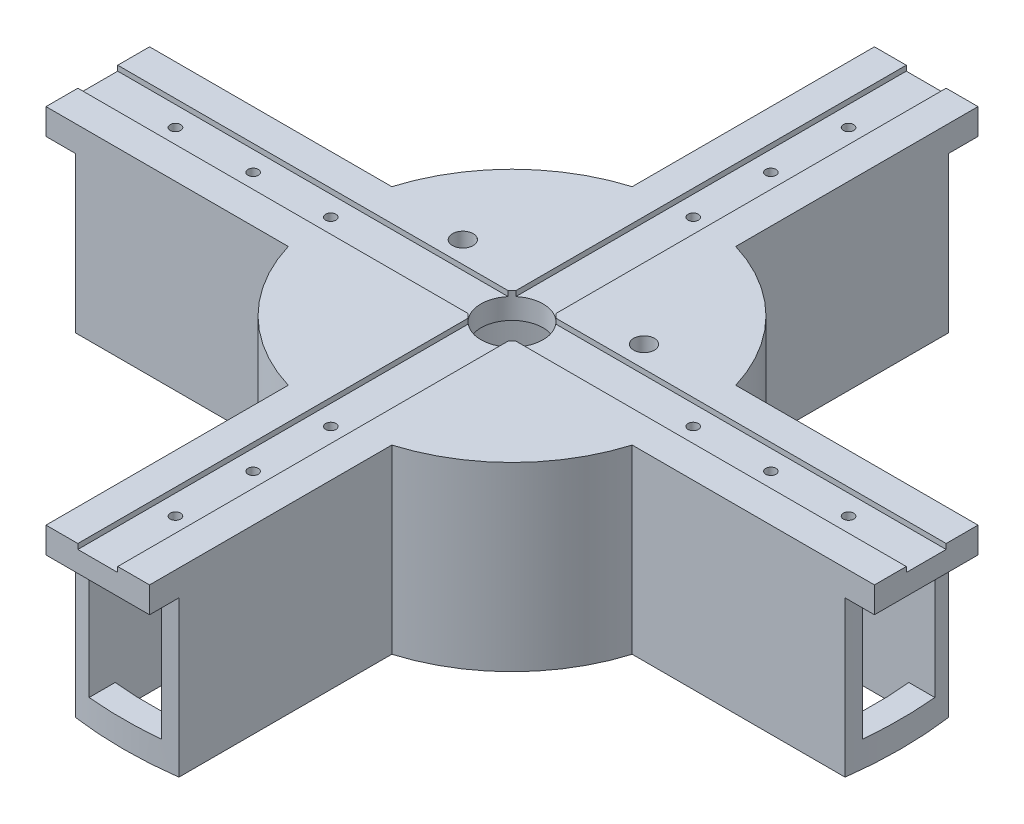
SolidWorks part; units mm, degrees
ref_plane "前视基准面" through (0, 0, 0) normal (0, 0, 1) x (1, 0, 0)
ref_plane "上视基准面" through (0, 0, 0) normal (0, 1, 0) x (1, 0, 0)
ref_plane "右视基准面" through (0, 0, 0) normal (1, 0, 0) x (0, 0, -1)
ref_plane "基准面4" through (0, -30, 0) normal (0, -1, 0) x (1, 0, 0)
sketch "草图1" plane through (0, -30, 0) normal (0, -1, 0) x (1, 0, 0)
  line L0 (-7, 74.6726) -> (-10, 74.6726)
  line L1 (-10, 74.6726) -> (-10, 33.2151)
  line L2 (-33.2151, 10) -> (-74.3303, 10)
  line L3 (-74.6726, 10) -> (-74.6726, 7)
  line L4 (-74.3303, -10) -> (-33.2151, -10)
  line L5 (-10, -33.2151) -> (-10, -74.3303)
  line L6 (10, -74.3303) -> (10, -33.2151)
  line L7 (33.2151, -10) -> (74.3303, -10)
  line L8 (74.6726, -10) -> (74.6726, -7)
  line L9 (74.3303, 10) -> (33.2151, 10)
  line L10 (10, 33.2151) -> (10, 74.3303)
  line L11 (-69.6491, 7) -> (-30.9049, 7)
  line L12 (-7, 30.9049) -> (-7, 69.6491)
  line L13 (7, 69.6491) -> (7, 30.9049)
  line L14 (30.9049, 7) -> (69.6491, 7)
  line L15 (69.6491, -7) -> (30.9049, -7)
  line L16 (7, -30.9049) -> (7, -69.6491)
  line L17 (-7, -69.6491) -> (-7, -30.9049)
  line L18 (-30.9049, -7) -> (-69.6491, -7)
  arc A0 (10, 74.3303) -> (-7, 74.6726) centre (0, 0) ccw
  arc A1 (-10, 33.2151) -> (-33.2151, 10) centre (0, 0) ccw
  arc A2 (-74.6726, 7) -> (-74.3303, -10) centre (0, 0) ccw
  arc A3 (-33.2151, -10) -> (-10, -33.2151) centre (0, 0) ccw
  arc A4 (-10, -74.3303) -> (10, -74.3303) centre (0, 0) ccw
  arc A5 (10, -33.2151) -> (33.2151, -10) centre (0, 0) ccw
  arc A6 (74.6726, -7) -> (74.3303, 10) centre (0, 0) ccw
  arc A7 (33.2151, 10) -> (10, 33.2151) centre (0, 0) ccw
  arc A8 (-30.9049, 7) -> (-7, 30.9049) centre (0, 0) cw
  arc A9 (-7, 69.6491) -> (7, 69.6491) centre (0, 0) cw
  arc A10 (7, 30.9049) -> (30.9049, 7) centre (0, 0) cw
  arc A11 (69.6491, 7) -> (69.6491, -7) centre (0, 0) cw
  arc A12 (30.9049, -7) -> (7, -30.9049) centre (0, 0) cw
  arc A13 (7, -69.6491) -> (-7, -69.6491) centre (0, 0) cw
  arc A14 (-7, -30.9049) -> (-30.9049, -7) centre (0, 0) cw
  arc A15 (-69.6491, -7) -> (-69.6491, 7) centre (0, 0) cw
  spline S0 degree 3 poles (-74.6726, 10) (-74.5585, 10) (-74.4444, 10) (-74.3303, 10) knots 0 0 0 0 1 1 1 1
  spline S1 degree 3 poles (74.6726, -10) (74.5585, -10) (74.4444, -10) (74.3303, -10) knots 0 0 0 0 1 1 1 1
extrude "凸台-拉伸1" add sketch "草图1" against normal blind 5
sketch "草图2" plane through (0, -25, 0) normal (0, 1, 0) x (-1, 0, 0)
  line L0 (74.6726, 7) -> (30.9049, 7)
  line L1 (7, 30.9049) -> (7, 74.6726)
  line L2 (7, 74.6726) -> (10, 74.6726)
  line L3 (10, 74.6726) -> (10, 33.2151)
  line L4 (33.2151, 10) -> (74.6726, 10)
  line L5 (74.6726, 10) -> (74.6726, 7)
  arc A0 (30.9049, 7) -> (7, 30.9049) centre (0, 0) ccw
  arc A1 (10, 33.2151) -> (33.2151, 10) centre (0, 0) cw
extrude "凸台-拉伸2" add sketch "草图2" along normal blind 25
sketch "草图3" plane through (0, -25, 0) normal (0, 1, 0) x (-1, 0, 0)
  line L0 (-74.6726, -7) -> (-30.9049, -7)
  line L1 (-7, -30.9049) -> (-7, -74.6726)
  line L2 (-10, -74.3303) -> (-10, -33.2151)
  line L3 (-33.2151, -10) -> (-74.6726, -10)
  line L4 (-74.6726, -10) -> (-74.6726, -7)
  arc A0 (-30.9049, -7) -> (-7, -30.9049) centre (0, 0) ccw
  arc A1 (-7, -74.6726) -> (-10, -74.3303) centre (0, 0) cw
  arc A2 (-10, -33.2151) -> (-33.2151, -10) centre (0, 0) cw
extrude "凸台-拉伸3" add sketch "草图3" along normal blind 25
sketch "草图4" plane through (0, -25, 0) normal (0, 1, 0) x (-1, 0, 0)
  line L0 (-30.9049, 7) -> (-74.6726, 7)
  line L1 (-74.3303, 10) -> (-33.2151, 10)
  line L2 (-10, 33.2151) -> (-10, 74.3303)
  line L3 (-7, 74.6726) -> (-7, 30.9049)
  arc A0 (-74.6726, 7) -> (-74.3303, 10) centre (0, 0) cw
  arc A1 (-33.2151, 10) -> (-10, 33.2151) centre (0, 0) cw
  arc A2 (-10, 74.3303) -> (-7, 74.6726) centre (0, 0) cw
  arc A3 (-7, 30.9049) -> (-30.9049, 7) centre (0, 0) ccw
extrude "凸台-拉伸4" add sketch "草图4" along normal blind 25
sketch "草图5" plane through (0, -25, 0) normal (0, 1, 0) x (-1, 0, 0)
  line L0 (30.9049, -7) -> (74.6726, -7)
  line L1 (74.3303, -10) -> (33.2151, -10)
  line L2 (10, -33.2151) -> (10, -74.3303)
  line L3 (7, -74.6726) -> (7, -30.9049)
  arc A0 (74.6726, -7) -> (74.3303, -10) centre (0, 0) cw
  arc A1 (33.2151, -10) -> (10, -33.2151) centre (0, 0) cw
  arc A2 (10, -74.3303) -> (7, -74.6726) centre (0, 0) cw
  arc A3 (7, -30.9049) -> (30.9049, -7) centre (0, 0) ccw
extrude "凸台-拉伸5" add sketch "草图5" along normal blind 25
sketch "草图6" plane through (0, 0, 0) normal (0, 1, 0) x (-1, 0, 0)
  line L0 (-74.6726, -10) -> (-74.6726, 7)
  line L1 (-74.3303, 10) -> (-33.2151, 10)
  line L2 (-10, 33.2151) -> (-10, 74.6726)
  line L3 (-10, 74.6726) -> (10, 74.6726)
  line L4 (10, 74.6726) -> (10, 33.2151)
  line L5 (33.2151, 10) -> (74.3303, 10)
  line L6 (74.6726, 10) -> (74.6726, -7)
  line L7 (74.3303, -10) -> (33.2151, -10)
  line L8 (10, -33.2151) -> (10, -74.6726)
  line L9 (10, -74.6726) -> (-10, -74.6726)
  line L10 (-10, -74.6726) -> (-10, -33.2151)
  line L11 (-33.2151, -10) -> (-74.3303, -10)
  arc A0 (-74.6726, 7) -> (-74.3303, 10) centre (0, 0) cw
  arc A1 (-33.2151, 10) -> (-10, 33.2151) centre (0, 0) cw
  arc A2 (10, 33.2151) -> (33.2151, 10) centre (0, 0) cw
  arc A3 (74.6726, -7) -> (74.3303, -10) centre (0, 0) cw
  arc A4 (33.2151, -10) -> (10, -33.2151) centre (0, 0) cw
  arc A5 (-10, -33.2151) -> (-33.2151, -10) centre (0, 0) cw
  spline S0 degree 3 poles (74.6726, 10) (74.5585, 10) (74.4444, 10) (74.3303, 10) knots 0 0 0 0 1 1 1 1
  spline S1 degree 3 poles (-74.6726, -10) (-74.5585, -10) (-74.4444, -10) (-74.3303, -10) knots 0 0 0 0 1 1 1 1
extrude "凸台-拉伸6" add sketch "草图6" along normal blind 5
sketch "草图7" plane through (0, 5, 0) normal (0, 1, 0) x (-1, 0, 0)
  line L0 (3.85, -3.85) -> (74.3303, -3.85)
  line L1 (74.6726, -3.85) -> (74.6726, 3.85)
  line L2 (74.3303, 3.85) -> (3.85, 3.85)
  line L3 (3.85, 3.85) -> (3.85, 74.6726)
  line L4 (3.85, 74.6726) -> (-3.85, 74.6726)
  line L5 (-3.85, 74.6726) -> (-3.85, 3.85)
  line L6 (-3.85, 3.85) -> (-74.3303, 3.85)
  line L7 (-74.6726, 3.85) -> (-74.6726, -3.85)
  line L8 (-74.3303, -3.85) -> (-3.85, -3.85)
  line L9 (-3.85, -3.85) -> (-3.85, -74.6726)
  line L10 (-3.85, -74.6726) -> (3.85, -74.6726)
  line L11 (3.85, -74.6726) -> (3.85, -3.85)
  spline S0 degree 3 poles (74.6726, -3.85) (74.5585, -3.85) (74.4444, -3.85) (74.3303, -3.85) knots 0 0 0 0 1 1 1 1
  spline S1 degree 3 poles (74.6726, 3.85) (74.5585, 3.85) (74.4444, 3.85) (74.3303, 3.85) knots 0 0 0 0 1 1 1 1
  spline S2 degree 3 poles (-74.6726, 3.85) (-74.5585, 3.85) (-74.4444, 3.85) (-74.3303, 3.85) knots 0 0 0 0 1 1 1 1
  spline S3 degree 3 poles (-74.6726, -3.85) (-74.5585, -3.85) (-74.4444, -3.85) (-74.3303, -3.85) knots 0 0 0 0 1 1 1 1
extrude "切除-拉伸1" cut sketch "草图7" against normal blind 1
sketch "草图8" plane through (0, -30, 0) normal (0, -1, 0) x (1, 0, 0)
  line L0 (-7, 74.6726) -> (-10, 74.6726)
  line L1 (-10, 74.6726) -> (-10, 74.3303)
  arc A0 (-10, 74.3303) -> (-7, 74.6726) centre (0, 0) cw
extrude "切除-拉伸2" cut sketch "草图8" against normal blind 5
sketch "草图9" plane through (0, -30, 0) normal (0, -1, 0) x (1, 0, 0)
  line L0 (-74.6726, 10) -> (-74.6726, 7)
  arc A0 (-74.6726, 7) -> (-74.3303, 10) centre (0, 0) cw
  spline S0 degree 3 poles (-74.6726, 10) (-74.5585, 10) (-74.4444, 10) (-74.3303, 10) knots 0 0 0 0 1 1 1 1
extrude "切除-拉伸3" cut sketch "草图9" against normal blind 5
sketch "草图10" plane through (0, -30, 0) normal (0, -1, 0) x (1, 0, 0)
  line L0 (74.6726, -10) -> (74.6726, -7)
  arc A0 (74.6726, -7) -> (74.3303, -10) centre (0, 0) cw
  spline S0 degree 3 poles (74.6726, -10) (74.5585, -10) (74.4444, -10) (74.3303, -10) knots 0 0 0 0 1 1 1 1
extrude "切除-拉伸4" cut sketch "草图10" against normal blind 5
sketch "草图11" plane through (0, -25, 0) normal (0, -1, 0) x (1, 0, 0)
  line L0 (-74.6726, 10) -> (-74.6726, 7)
  arc A0 (-74.6726, 7) -> (-74.3303, 10) centre (0, 0) cw
  spline S0 degree 3 poles (-74.6726, 10) (-74.5585, 10) (-74.4444, 10) (-74.3303, 10) knots 0 0 0 0 1 1 1 1
extrude "切除-拉伸5" cut sketch "草图11" against normal blind 25
sketch "草图12" plane through (-74.6726, 0, 0) normal (-1, 0, 0) x (0, 0, 1)
  line L0 (-3.85, 5) -> (-7, 5)
  line L1 (-7, 5) -> (-7, 0)
  line L2 (-7, 0) -> (7, 0)
  line L3 (7, 0) -> (10, 0)
  line L4 (10, 0) -> (10, 5)
  line L5 (10, 5) -> (3.85, 5)
  line L6 (3.85, 5) -> (3.85, 4)
  line L7 (3.85, 4) -> (-3.85, 4)
  line L8 (-3.85, 4) -> (-3.85, 5)
extrude "切除-拉伸6" cut sketch "草图12" against normal blind 0.3423
sketch "草图13" plane through (0, 5, 0) normal (0, 1, 0) x (-1, 0, 0)
  line L0 (74.6726, -7) -> (74.3303, -7)
  line L1 (74.3303, -7) -> (74.3303, -10)
  arc A0 (74.3303, -10) -> (74.6726, -7) centre (0, 0) ccw
extrude "切除-拉伸7" cut sketch "草图13" against normal blind 5
sketch "草图14" plane through (-74.3303, 0, 0) normal (-1, 0, 0) x (0, 0, 1)
  line L0 (3.85, 4) -> (3.85, 5)
  line L1 (3.85, 5) -> (10, 5)
  line L2 (10, 5) -> (10, 0)
  line L3 (10, 0) -> (7, 0)
  line L4 (7, 0) -> (-7, 0)
  line L5 (-7, 0) -> (-10, 0)
  line L6 (-10, 0) -> (-10, 5)
  line L7 (-10, 5) -> (-3.85, 5)
  line L8 (-3.85, 5) -> (-3.85, 4)
  line L9 (-3.85, 4) -> (3.85, 4)
extrude "凸台-拉伸7" add sketch "草图14" along normal blind 0.3423
sketch "草图15" plane through (0, -25, 0) normal (0, -1, 0) x (1, 0, 0)
  line L0 (74.6726, -10) -> (74.6726, -7)
  arc A0 (74.6726, -7) -> (74.3303, -10) centre (0, 0) cw
  spline S0 degree 3 poles (74.6726, -10) (74.5585, -10) (74.4444, -10) (74.3303, -10) knots 0 0 0 0 1 1 1 1
extrude "切除-拉伸8" cut sketch "草图15" against normal blind 25
sketch "草图16" plane through (74.6726, 0, 0) normal (1, 0, 0) x (0, 0, -1)
  line L0 (-3.85, 5) -> (-7, 5)
  line L1 (-7, 5) -> (-7, 0)
  line L2 (-7, 0) -> (7, 0)
  line L3 (7, 0) -> (10, 0)
  line L4 (10, 0) -> (10, 5)
  line L5 (10, 5) -> (3.85, 5)
  line L6 (3.85, 5) -> (3.85, 4)
  line L7 (3.85, 4) -> (-3.85, 4)
  line L8 (-3.85, 4) -> (-3.85, 5)
extrude "切除-拉伸9" cut sketch "草图16" against normal blind 0.3423
sketch "草图17" plane through (0, 5, 0) normal (0, 1, 0) x (-1, 0, 0)
  line L0 (-74.6726, 7) -> (-74.3303, 7)
  line L1 (-74.3303, 7) -> (-74.3303, 10)
  arc A0 (-74.3303, 10) -> (-74.6726, 7) centre (0, 0) ccw
extrude "切除-拉伸10" cut sketch "草图17" against normal blind 5
sketch "草图18" plane through (74.3303, 0, 0) normal (1, 0, 0) x (0, 0, -1)
  line L0 (-3.85, 5) -> (-3.85, 4)
  line L1 (-3.85, 4) -> (3.85, 4)
  line L2 (3.85, 4) -> (3.85, 5)
  line L3 (3.85, 5) -> (10, 5)
  line L4 (10, 5) -> (10, 0)
  line L5 (10, 0) -> (7, 0)
  line L6 (7, 0) -> (-7, 0)
  line L7 (-7, 0) -> (-10, 0)
  line L8 (-10, 0) -> (-10, 5)
  line L9 (-10, 5) -> (-3.85, 5)
extrude "凸台-拉伸8" add sketch "草图18" along normal blind 0.3423
sketch "草图19" plane through (0, 0, -74.6726) normal (0, 0, -1) x (-1, 0, 0)
  line L0 (3.85, 4) -> (3.85, 5)
  line L1 (3.85, 5) -> (10, 5)
  line L2 (10, 5) -> (10, 0)
  line L3 (10, 0) -> (-10, 0)
  line L4 (-10, 0) -> (-10, 5)
  line L5 (-10, 5) -> (-3.85, 5)
  line L6 (-3.85, 5) -> (-3.85, 4)
  line L7 (-3.85, 4) -> (3.85, 4)
extrude "凸台-拉伸9" add sketch "草图19" along normal blind 5.3274
sketch "草图20" plane through (74.6726, 0, 0) normal (1, 0, 0) x (0, 0, -1)
  line L0 (-3.85, 5) -> (-3.85, 4)
  line L1 (-3.85, 4) -> (3.85, 4)
  line L2 (3.85, 4) -> (3.85, 5)
  line L3 (3.85, 5) -> (10, 5)
  line L4 (10, 5) -> (10, 0)
  line L5 (10, 0) -> (-10, 0)
  line L6 (-10, 0) -> (-10, 5)
  line L7 (-10, 5) -> (-3.85, 5)
extrude "凸台-拉伸10" add sketch "草图20" along normal blind 5.3274
sketch "草图21" plane through (-74.6726, 0, 0) normal (-1, 0, 0) x (0, 0, 1)
  line L0 (3.85, 4) -> (3.85, 5)
  line L1 (3.85, 5) -> (10, 5)
  line L2 (10, 5) -> (10, 0)
  line L3 (10, 0) -> (-10, 0)
  line L4 (-10, 0) -> (-10, 5)
  line L5 (-10, 5) -> (-3.85, 5)
  line L6 (-3.85, 5) -> (-3.85, 4)
  line L7 (-3.85, 4) -> (3.85, 4)
extrude "凸台-拉伸11" add sketch "草图21" along normal blind 5.3274
sketch "草图22" plane through (0, -25, 0) normal (0, -1, 0) x (1, 0, 0)
  line L0 (-7, 74.6726) -> (-10, 74.6726)
  line L1 (-10, 74.6726) -> (-10, 74.3303)
  arc A0 (-10, 74.3303) -> (-7, 74.6726) centre (0, 0) cw
extrude "切除-拉伸11" cut sketch "草图22" against normal blind 25
sketch "草图23" plane through (0, 0, 74.6726) normal (0, 0, 1) x (1, 0, 0)
  line L0 (3.85, 4) -> (3.85, 5)
  line L1 (3.85, 5) -> (10, 5)
  line L2 (10, 5) -> (10, 0)
  line L3 (10, 0) -> (-10, 0)
  line L4 (-10, 0) -> (-10, 5)
  line L5 (-10, 5) -> (-3.85, 5)
  line L6 (-3.85, 5) -> (-3.85, 4)
  line L7 (-3.85, 4) -> (3.85, 4)
extrude "凸台-拉伸12" add sketch "草图23" along normal blind 5.3274
hole_wizard "Ø2.0 (2) 直径孔1" positions "草图25" profile "草图24" hole size "Ø2.0" standard "ANSI Metric"
sketch "草图25" plane through (0, 0, 0) normal (0, -1, 0) x (-1, 0, 0)
  point P0 (-50, 0)
  point P1 (-35, 0)
  point P2 (-65, 0)
  point P3 (50, 0)
  point P4 (35, 0)
  point P5 (65, 0)
sketch "草图24" plane through (50, 0, 0) normal (1, 0, 0) x (0, 0, -1)
  line L0 (0, 0) -> (0, 5)
  line L1 (0, 5) -> (1, 5)
  line L2 (1, 5) -> (1, 0)
  line L5 (1, 0) -> (0, 0)
  line L11 (0, -6.35) -> (0, 107.95) construction
  dimension "通孔孔直径" = 2
  dimension "通孔孔深度" = 5
hole_wizard "Ø12.0 (12) 直径孔1" positions "草图27" profile "草图26" hole size "Ø12.0" standard "ANSI Metric"
sketch "草图27" plane through (0, 0, 0) normal (0, -1, 0) x (-1, 0, 0)
  point P0 (0, 0)
sketch "草图26" plane through (0, 0, 0) normal (1, 0, 0) x (0, 0, -1)
  line L0 (0, 0) -> (0, 5)
  line L1 (0, 5) -> (6, 5)
  line L2 (6, 5) -> (6, 0)
  line L5 (6, 0) -> (0, 0)
  line L11 (0, -6.35) -> (0, 107.95) construction
  dimension "通孔孔直径" = 12
  dimension "通孔孔深度" = 5
hole_wizard "Ø2.0 (2) 直径孔2" positions "草图29" profile "草图28" hole size "Ø2.0" standard "ANSI Metric"
sketch "草图29" plane through (0, 4, 0) normal (0, 1, 0) x (1, 0, 0)
  point P0 (0, -65)
  point P1 (0, 65)
  point P2 (0, 35)
  point P3 (0, 50)
  point P4 (0, -50)
  point P5 (0, -35)
sketch "草图28" plane through (0, 4, 65) normal (1, 0, 0) x (0, 0, 1)
  line L0 (0, 0) -> (0, 34)
  line L1 (0, 34) -> (1, 34)
  line L2 (1, 34) -> (1, 0)
  line L5 (1, 0) -> (0, 0)
  line L11 (0, -6.35) -> (0, 107.95) construction
  dimension "通孔孔直径" = 2
  dimension "通孔孔深度" = 34
hole_wizard "Ø4.0 (4) 直径孔1" positions "草图31" profile "草图30" hole size "Ø4.0" standard "ANSI Metric"
sketch "草图31" plane through (0, 0, 0) normal (0, -1, 0) x (-1, 0, 0)
  point P0 (-17.5, 8)
  point P1 (17.5, 8)
sketch "草图30" plane through (17.5, 0, -8) normal (1, 0, 0) x (0, 0, -1)
  line L0 (0, 0) -> (0, 5)
  line L1 (0, 5) -> (2, 5)
  line L2 (2, 5) -> (2, 0)
  line L5 (2, 0) -> (0, 0)
  line L11 (0, -6.35) -> (0, 107.95) construction
  dimension "通孔孔直径" = 4
  dimension "通孔孔深度" = 5
